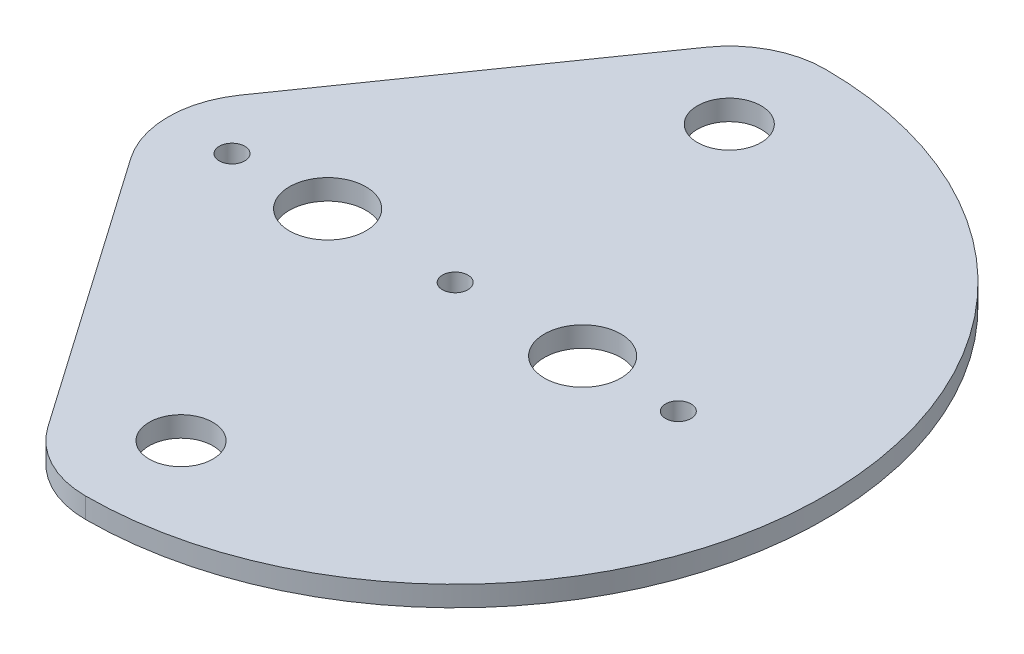
SolidWorks part; units mm, degrees
ref_plane "Front Plane" through (0, 0, 0) normal (0, 0, 1) x (1, 0, 0)
ref_plane "Top Plane" through (0, 0, 0) normal (0, 1, 0) x (1, 0, 0)
ref_plane "Right Plane" through (0, 0, 0) normal (1, 0, 0) x (0, 0, -1)
sketch "Sketch1" plane through (0, 0, 0) normal (0, 1, 0) x (1, 0, 0)
  line L0 (0, -21.5) -> (0, 21.5) construction
  line L1 (10, 0) -> (-10, 0) construction
  line L2 (-21.151, 4.2914) -> (-6.151, 25.7914)
  line L3 (6.151, 25.7914) -> (21.151, 4.2914)
  line L4 (21.151, -4.2914) -> (6.151, -25.7914)
  line L5 (-6.151, -25.7914) -> (-21.151, -4.2914)
  line L6 (-15, 0) -> (-10, 0) construction
  line L7 (10, 0) -> (15, 0) construction
  line L8 (-17.5, 0) -> (17.5, 0) construction
  circle A0 centre (0, 21.5) radius 2.5
  circle A1 centre (0, -21.5) radius 2.5
  circle A3 centre (-10, 0) radius 3
  circle A4 centre (10, 0) radius 3
  arc A5 (-6.151, 25.7914) -> (6.151, 25.7914) centre (0, 21.5) cw
  arc A6 (6.151, -25.7914) -> (-6.151, -25.7914) centre (0, -21.5) cw
  arc A9 (-21.151, -4.2914) -> (-21.151, 4.2914) centre (-15, 0) cw
  arc A10 (21.151, -4.2914) -> (21.151, 4.2914) centre (15, 0) ccw
  circle A11 centre (-17.5, 0) radius 1
  circle A12 centre (0, 0) radius 1
  circle A13 centre (17.5, 0) radius 1
  dimension "D2" = 5
  dimension "D4" = 5
  dimension "D5" = 35
  dimension "Extrusion Holes" = 6
  dimension "D6" = 2
  dimension "D1" = 43
  dimension "D3" = 20
  dimension "Extra Wideness" = 5
extrude "Boss-Extrude1" add sketch "Sketch1" along normal mid plane 1.6
sketch "Sketch2" plane through (0, 0.8, 0) normal (0, 1, 0) x (1, 0, 0)
  line L0 (0, -29) -> (22.5, 0)
  line L1 (22.5, 0) -> (0, 29)
  arc A0 (0, 29) -> (0, -29) centre (0, 0) cw
  arc A2 (6.151, 25.7914) -> (-6.151, 25.7914) centre (0, 21.5) ccw construction
  arc A4 (-6.151, -25.7914) -> (6.151, -25.7914) centre (0, -21.5) ccw construction
  arc A6 (21.151, -4.2914) -> (21.151, 4.2914) centre (15, 0) ccw construction
extrude "Boss-Extrude2" add sketch "Sketch2" against normal through all
